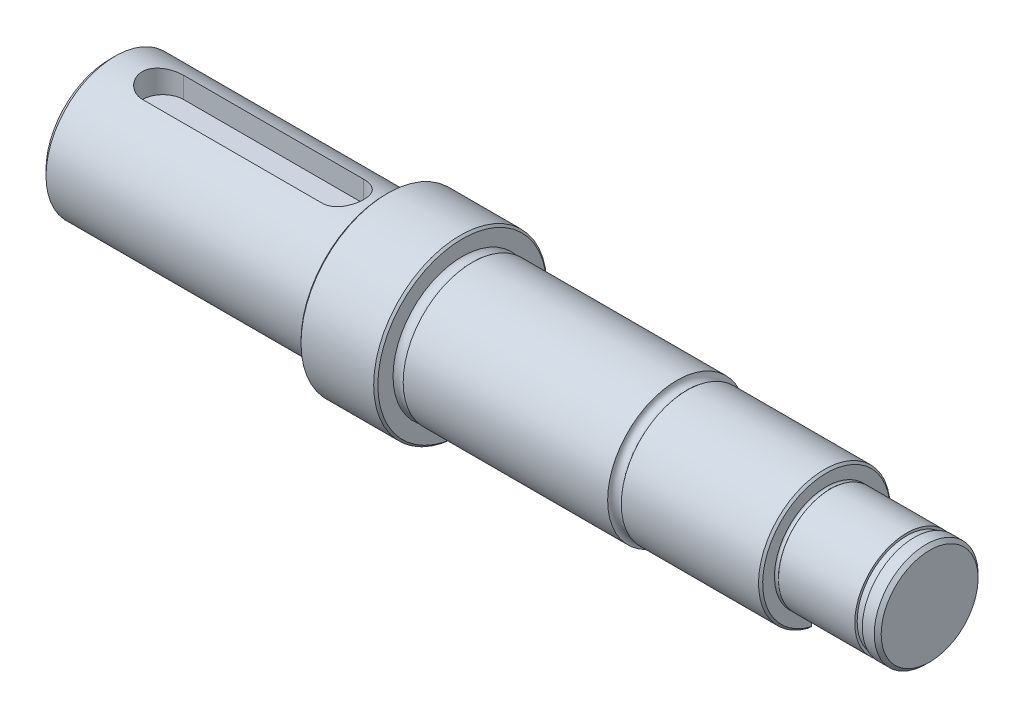
SolidWorks part; units mm, degrees
ref_plane "Plan de face" through (0, 0, 0) normal (0, 0, 1) x (1, 0, 0)
ref_plane "Plan de dessus" through (0, 0, 0) normal (0, 1, 0) x (1, 0, 0)
ref_plane "Plan de droite" through (0, 0, 0) normal (1, 0, 0) x (0, 0, -1)
sketch "Esquisse1" plane through (0, 0, 0) normal (0, 0, 1) x (1, 0, 0)
  line L0 (-8.6819, 0) -> (124.3093, 0) construction
  line L1 (0, 0) -> (0, 9.2)
  line L2 (0, 9.2) -> (0.8, 10)
  line L3 (0.8, 10) -> (38.4003, 10)
  line L4 (39.84, 10) -> (39.84, 12.2)
  line L5 (40.14, 12.5) -> (50.64, 12.5)
  line L6 (50.94, 12.2) -> (50.94, 10)
  line L7 (52.4029, 10) -> (81.94, 10)
  line L8 (83.4136, 9.5) -> (103.24, 9.5)
  line L9 (116.24, 7.5) -> (117.96, 7.5)
  line L10 (103.54, 9.2) -> (103.54, 7.5)
  line L11 (118.46, 7) -> (118.46, 0)
  line L12 (118.46, 0) -> (0, 0)
  line L13 (117.96, 7.5) -> (118.46, 7)
  line L14 (103.24, 9.5) -> (103.54, 9.2)
  line L15 (50.64, 12.5) -> (50.94, 12.2)
  line L16 (39.84, 12.2) -> (40.14, 12.5)
  line L17 (115.14, 7.5) -> (104.1205, 7.5)
  line L19 (115.14, 7.5) -> (115.14, 7.15)
  line L20 (115.14, 7.15) -> (116.24, 7.15)
  line L21 (116.24, 7.5) -> (116.24, 7.15)
  arc A0 (81.94, 10) -> (83.4136, 9.5) centre (82.7616, 10) ccw
  arc A1 (103.54, 7.5) -> (104.1205, 7.5) centre (103.8303, 7.6397) ccw
  arc A3 (39.84, 10) -> (38.4003, 10) centre (39.1201, 10.63) cw
  arc A4 (50.94, 10) -> (52.4029, 10) centre (51.6714, 10.8141) ccw
  point P8 (39.84, 12.5)
  point P9 (50.94, 12.5)
  point P15 (103.54, 9.5)
  dimension "D1" = 31
  dimension "D11" = 15
  dimension "D17" = 0.3221
  dimension "D2" = 20
  dimension "D3" = 45
  dimension "D4" = 0.8
  dimension "D5" = 39.84
  dimension "D6" = 25
  dimension "D7" = 11.1
  dimension "D8" = 20
  dimension "D9" = 19
  dimension "D10" = 21.6
  dimension "D12" = 2.22
  dimension "D13" = 1.1
  dimension "D22" = 0.5
  dimension "D15" = 45
  dimension "D19" = 0.3
  dimension "D20" = 0.3
  dimension "D21" = 0.3
  dimension "D14" = 14.3
  dimension "D16" = 12.7
  dimension "D18" = 0.1397
revolve "Révolution1" add sketch "Esquisse1" angle 360 about L0
hole_wizard "Trou taraudé M61" positions "Esquisse7" profile "Esquisse6" tap size "M6" standard "ISO"
sketch "Esquisse7" plane through (0, 0, 0) normal (-1, 0, 0) x (0, 0, 1)
  point P1 (0, 0)
sketch "Esquisse6" plane through (0, 0, 0) normal (0, 1, 0) x (0, 0, 1)
  line L0 (0, 0) -> (0, 18.5022)
  line L1 (0, 18.5022) -> (2.5, 17)
  line L2 (2.5, 17) -> (2.5, 0)
  line L5 (2.5, 0) -> (0, 0)
  line L10 (0, 18.5022) -> (-2.5, 17) construction
  line L11 (0, -6.35) -> (0, 107.95) construction
  dimension "Diamètre du trou pour taraudage" = 5
  dimension "Profondeur du trou pour taraudage" = 17
  dimension "Angle de pointe" = 118
cosmetic thread "Filetage de perçage1" parameters "D1"=12, "D2"=6
chamfer "Chanfrein1" distance 1.5 angle 45 1 edges at (0, 0, 2.5)
ref_plane "Plan1" through (19.6001, 10, 0) normal (0, 1, 0) x (0, 0, -1)
sketch "Esquisse8" plane through (19.6001, 10, 0) normal (0, 1, 0) x (0, 0, -1)
  line L0 (3, 11.9001) -> (3, -14.0999)
  line L1 (-3, 11.9001) -> (-3, -14.0999)
  line L3 (0, 28.2821) -> (0, -104.7092) construction
  line L4 (0, 23.7218) -> (0, -100.3561) construction
  line L5 (0, 2.6001) -> (0, 18.1001) construction
  line L6 (9.2, 19.6001) -> (-9.2, 19.6001) construction
  arc A0 (3, 11.9001) -> (-3, 11.9001) centre (0, 11.9001) ccw
  arc A1 (-3, -14.0999) -> (3, -14.0999) centre (0, -14.0999) ccw
  dimension "D1" = 6
  dimension "D2" = 26
  dimension "D3" = 7.7
extrude "Enlèv. mat.-Extru.1" cut sketch "Esquisse8" against normal blind 3.5
ref_plane "Plan4" through (93.3268, -9.5, 0) normal (0, -1, 0) x (0, 0, 1)
sketch "Esquisse9" plane through (93.3268, -9.5, 0) normal (0, -1, 0) x (0, 0, 1)
  line L0 (3, 7.8868) -> (3, -8.1132)
  line L1 (-3, 7.8868) -> (-3, -8.1132)
  line L2 (0, 102.0087) -> (0, -30.9825) construction
  line L3 (0, -27.5371) -> (0, 14.5469) construction
  line L4 (10, 11.3868) -> (-10, 11.3868) construction
  arc A0 (-3, 7.8868) -> (3, 7.8868) centre (0, 7.8868) cw
  arc A1 (3, -8.1132) -> (-3, -8.1132) centre (0, -8.1132) cw
  dimension "D1" = 6
  dimension "D2" = 16
  dimension "D3" = 3.5
extrude "Enlèv. mat.-Extru.2" cut sketch "Esquisse9" against normal blind 3.5
